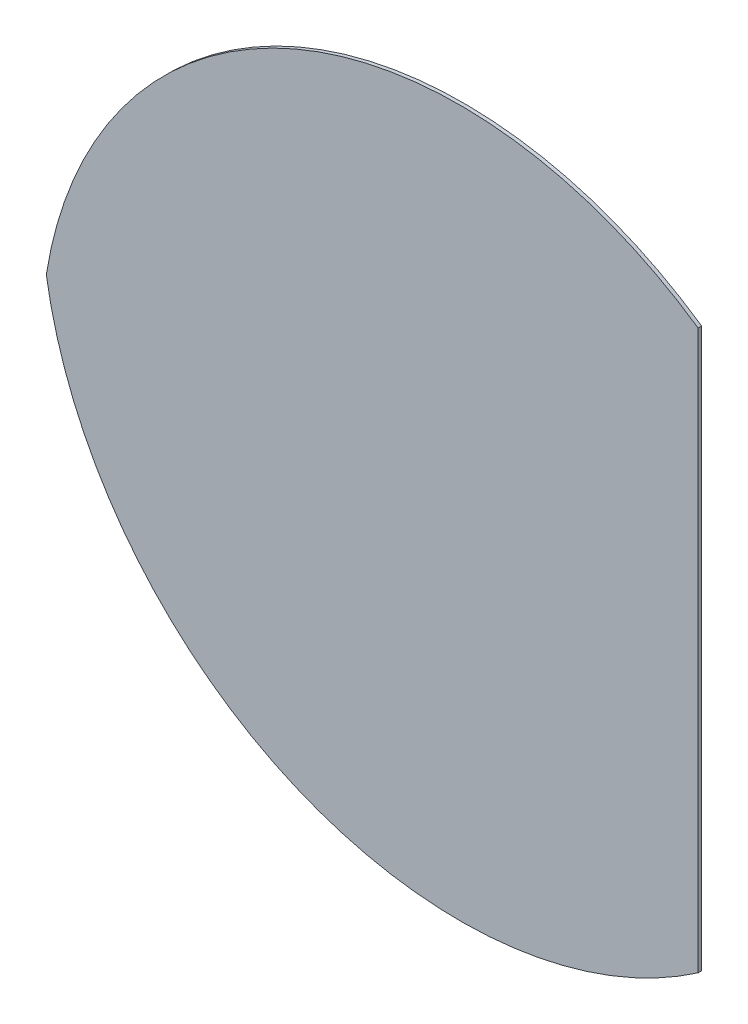
SolidWorks part; units mm, degrees
ref_plane "Front Plane" through (0, 0, 0) normal (0, 0, 1) x (1, 0, 0)
ref_plane "Top Plane" through (0, 0, 0) normal (0, 1, 0) x (1, 0, 0)
ref_plane "Right Plane" through (0, 0, 0) normal (1, 0, 0) x (0, 0, -1)
sketch "Sketch1" plane through (0, 0, 0) normal (0, 0, 1) x (1, 0, 0)
  line L9 (21.1964, 90.7691) -> (21.1964, 168.8426) construction
  line L11 (-46.0168, 111.701) -> (-193.0896, 111.701) construction
  line L12 (-46.0168, 30.5502) -> (-46.0168, 146.0631) construction
  line L13 (-46.0168, -6.6772) -> (-46.0168, -105.0487) construction
  line L14 (-46.0168, -87.8897) -> (-192.8512, -87.8897) construction
  line L15 (21.1964, 90.7691) -> (21.1964, -66.971)
  arc A0 (-162.9535, 11.7403) -> (21.1964, 90.7691) centre (-46.0168, -6.6772) cw
  arc A1 (21.1964, -66.971) -> (-162.9535, 11.7403) centre (-46.0168, 30.5502) cw
  point P2 (0, 0)
  point P3 (0, 0)
  point P4 (0, 0)
  point P5 (20.4912, 83.8311)
  point P6 (0, 0)
  point P7 (0, 0)
  dimension "D12" = 199.5908
extrude "Boss-Extrude1" add sketch "Sketch1" along normal blind 1
